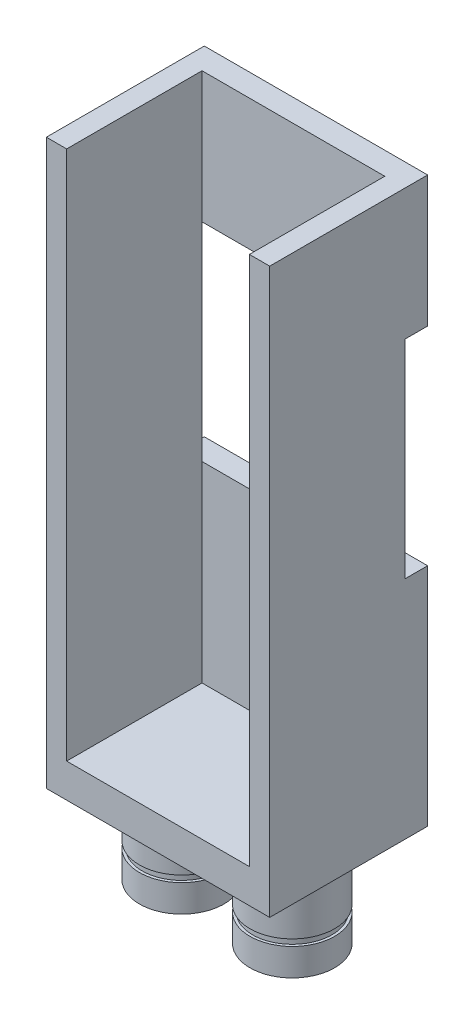
SolidWorks part; units mm, degrees
ref_plane "Front Plane" through (0, 0, 0) normal (0, 0, 1) x (1, 0, 0)
ref_plane "Top Plane" through (0, 0, 0) normal (0, 1, 0) x (1, 0, 0)
ref_plane "Right Plane" through (0, 0, 0) normal (1, 0, 0) x (0, 0, -1)
sketch "Sketch2" plane through (0, 0, 0) normal (0, 1, 0) x (1, 0, 0)
  line L1 (-12.573, 8.89) -> (12.573, 8.89)
  line L2 (-12.573, 8.89) -> (-12.573, -8.89)
  line L3 (-12.573, -8.89) -> (12.573, -8.89)
  line L4 (12.573, 8.89) -> (12.573, -8.89)
  point P4 (0, 8.89)
  point P6 (12.573, 0)
  dimension "D1" = 25.146
  dimension "D2" = 17.78
extrude "Boss-Extrude1" add sketch "Sketch2" along normal blind 63.5
sketch "Sketch3" plane through (0, 63.5, 0) normal (0, 1, 0) x (1, 0, 0)
  line L0 (12.573, 8.89) -> (-12.573, 8.89) construction
  line L1 (-10.287, 6.35) -> (10.287, 6.35)
  line L2 (-10.287, 6.35) -> (-10.287, -8.89)
  line L3 (-10.287, -8.89) -> (10.287, -8.89)
  line L4 (10.287, 6.35) -> (10.287, -8.89)
  line L5 (-12.573, -8.89) -> (12.573, -8.89) construction
  line L6 (12.573, -8.89) -> (12.573, 8.89) construction
  point P4 (0, 6.35)
  point P7 (0, 8.89)
  dimension "D1" = 2.54
  dimension "D2" = 2.286
extrude "Cut-Extrude1" cut sketch "Sketch3" against normal blind 59.69
sketch "Sketch4" plane through (0, 0, 0) normal (0, -1, 0) x (-1, 0, 0)
  line L0 (12.573, 8.89) -> (12.573, -8.89) construction
  line L1 (-12.573, -8.89) -> (-12.573, 8.89) construction
  circle A0 centre (6.223, 0) radius 4.7625
  circle A1 centre (-6.223, 0) radius 4.7625
  point P9 (12.573, 0)
  point P11 (-12.573, 0)
  dimension "D1" = 9.525
  dimension "D2" = 9.525
  dimension "D3" = 6.35
  dimension "D4" = 6.35
extrude "Boss-Extrude2" add sketch "Sketch4" along normal blind 10.16
sketch3d "3DSketch1"
  circle A0 centre (-6.223, -6.35, 0) radius 5.08
  circle A1 centre (6.223, -6.35, 0) radius 5.08
  circle A2 centre (-6.223, -10.16, 0) radius 4.7625 construction
  circle A3 centre (6.223, -10.16, 0) radius 4.7625 construction
  point P2 (-6.223, -11.43, 0)
  point P5 (6.223, -11.43, 0)
  point P9 (-6.223, -14.9225, 0)
  point P13 (6.223, -14.9225, 0)
  dimension "D2" = 10.16
  dimension "D3" = 10.16
  dimension "D1" = 6.35
extrude "Cut-Extrude2" cut sketch "3DSketch1" along direction (0, -1, 0) on the side of the normal blind 0.7366
sketch "Sketch5" plane through (0, -6.35, 0) normal (0, -1, 0) x (-1, 0, 0)
  circle A0 centre (6.223, 0) radius 4.4577
  circle A1 centre (-6.223, 0) radius 4.4704
  dimension "D1" = 8.9154
  dimension "D2" = 8.9408
extrude "Boss-Extrude3" add sketch "Sketch5" along normal up to surface (0.7366 mm away) up to face at (-6.223, -7.0866, -4.7625)
sketch "Sketch6" plane through (0, 0, -8.89) normal (0, 0, -1) x (-1, 0, 0)
  line L0 (-12.573, 63.5) -> (-12.573, 0) construction
  line L1 (-12.573, 48.768) -> (12.573, 48.768)
  line L2 (-12.573, 48.768) -> (-12.573, 25.4)
  line L3 (-12.573, 25.4) -> (12.573, 25.4)
  line L4 (12.573, 48.768) -> (12.573, 25.4)
  line L5 (12.573, 63.5) -> (12.573, 0) construction
  line L6 (-12.573, 63.5) -> (12.573, 63.5) construction
  dimension "D1" = 14.732
  dimension "D2" = 23.368
extrude "Cut-Extrude3" cut sketch "Sketch6" against normal up to surface (2.54 mm away) up to face at (0, 33.655, -6.35)
